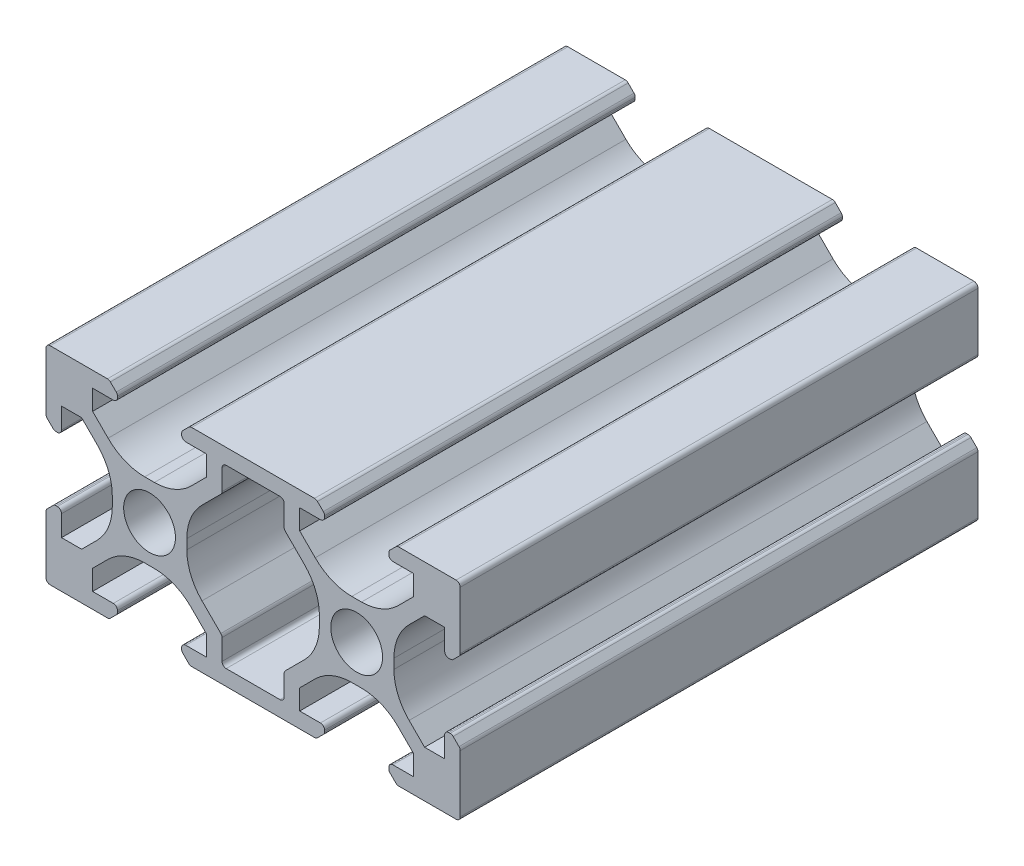
SolidWorks part; units mm, degrees
material "6063-T83"
ref_plane "Plano frontal" through (0, 0, 0) normal (0, 0, 1) x (1, 0, 0)
ref_plane "Plano superior" through (0, 0, 0) normal (0, 1, 0) x (1, 0, 0)
ref_plane "Plano direito" through (0, 0, 0) normal (1, 0, 0) x (0, 0, -1)
sketch "Esboço1" plane through (0, 0, 0) normal (0, 0, 1) x (1, 0, 0)
  line L0 (-9.0343, 3.1) -> (-8.9, 3.1)
  line L3 (-10, 10) -> (-4.0657, 10)
  line L5 (-10, -10) -> (10, 10) construction
  line L6 (-10, 10) -> (10, -10) construction
  line L7 (-8.5, 3.5) -> (-8.5, 5.5)
  line L8 (-10, 0) -> (10, 0) construction
  line L9 (0, 10) -> (0, -10) construction
  line L12 (-8.5, 5.5) -> (-6.5607, 5.5)
  line L15 (-6.5607, 5.5) -> (-5.0645, 4.0038)
  line L16 (-3.6, 0.4683) -> (-3.6, 0)
  line L17 (-0.4683, 3.6) -> (0, 3.6)
  line L18 (-5.5, 6.5607) -> (-4.0038, 5.0645)
  line L21 (-5.5, 8.5) -> (-5.5, 6.5607)
  line L24 (-3.5, 8.5) -> (-5.5, 8.5)
  line L25 (-3.1, 9.0343) -> (-3.1, 8.9)
  line L44 (-10, 4.0657) -> (-10, 10)
  line L45 (-9.8828, 3.7828) -> (-9.3172, 3.2172)
  line L46 (-3.7828, 9.8828) -> (-3.2172, 9.3172)
  line L47 (-3.6, 0) -> (-2.5, 0)
  line L48 (0, 3.6) -> (0, 2.5)
  arc A0 (-3.5, 8.5) -> (-3.1, 8.9) centre (-3.5, 8.9) ccw
  arc A1 (-3.7828, 9.8828) -> (-4.0657, 10) centre (-4.0657, 9.6) ccw
  arc A2 (-10, 4.0657) -> (-9.8828, 3.7828) centre (-9.6, 4.0657) ccw
  arc A3 (-8.5, 3.5) -> (-8.9, 3.1) centre (-8.9, 3.5) cw
  arc A4 (-3.2172, 9.3172) -> (-3.1, 9.0343) centre (-3.5, 9.0343) cw
  arc A5 (-9.3172, 3.2172) -> (-9.0343, 3.1) centre (-9.0343, 3.5) ccw
  arc A6 (-3.6, 0.4683) -> (-5.0645, 4.0038) centre (-8.6, 0.4683) ccw
  arc A7 (-4.0038, 5.0645) -> (-0.4683, 3.6) centre (-0.4683, 8.6) ccw
  circle A8 centre (0, 0) radius 2.5
  point P6 (-10, 3.1)
  point P28 (-3.1, 8.5)
  point P31 (-3.1, 10)
  point P33 (-3.9, 10)
  point P36 (-10, 3.9)
  point P39 (-8.5, 3.1)
  point P42 (-3.1, 9.2)
  point P45 (-9.2, 3.1)
  point P48 (-3.6, 2.5393)
  point P51 (-2.5393, 3.6)
  dimension "D5" = 10
  dimension "D9" = 0.4
  dimension "D10" = 0.4
  dimension "D11" = 5
  dimension "D12" = 5
  dimension "D13" = 5
  dimension "D1" = 6.9
  dimension "D2" = 1.5
  dimension "D3" = 3.6
  dimension "D4" = 1.5
  dimension "D6" = 2.4
  dimension "D7" = 3.6
  dimension "D8" = 45
extrude "Ressalto-extrusão1" add sketch "Esboço1" along normal blind 50
sketch "Esboço3" plane through (0, 0, 0) normal (1, 0, 0) x (0, 0, -1)
  line L0 (0, 0) -> (-1000, 0) construction
  dimension "D1" = 1000
pattern_circular "PadrãoCircular1" count 4 every 90 about axis through (0, 0, 0) along (0, 0, 1) of "Ressalto-extrusão1"
pattern_linear "Padrão linear1" count 2 spacing 20 along (1, 0, 0) of "Ressalto-extrusão1", "PadrãoCircular1"
sketch "Esboço4" plane through (0, 0, 0) normal (0, 0, -1) x (-1, 0, 0)
  line L0 (-13.4393, 5.5) -> (-13, 5.9393)
  line L1 (-13, 8.5) -> (-13, 5.9393)
  line L2 (-10, 10) -> (-10, -10) construction
  line L3 (-4.0657, 10) -> (-15.9343, 10) construction
  line L4 (-15.9343, -10) -> (-4.0657, -10) construction
  line L5 (-11.5, 5.5) -> (-13.4393, 5.5) construction
  line L6 (-14.5, 8.5) -> (-14.5, 6.5607) construction
  line L7 (-7, 8.5) -> (-7, 5.9393)
  line L8 (-6.5607, 5.5) -> (-7, 5.9393)
  line L9 (-13, 8.5) -> (-7, 8.5)
  line L10 (-20, 0) -> (0, 0) construction
  line L11 (-13, -8.5) -> (-7, -8.5)
  line L12 (-6.5607, -5.5) -> (-7, -5.9393)
  line L13 (-7, -8.5) -> (-7, -5.9393)
  line L14 (-13, -8.5) -> (-13, -5.9393)
  line L15 (-13.4393, -5.5) -> (-13, -5.9393)
  line L16 (-13.4393, 5.5) -> (-13.4393, -5.5)
  line L17 (-6.5607, -5.5) -> (-6.5607, 5.5)
  dimension "D1" = 45
  dimension "D2" = 1.5
  dimension "D3" = 1.5
extrude "Corte-extrusão1" cut sketch "Esboço4" against normal through all
fillet "Filete1" radius 0.4 8 edges at (13, -5.9393, 25) (13, -8.5, 25) (7, -8.5, 25) (7, -5.9393, 25) (7, 8.5, 25) (7, 5.9393, 25) (13, 8.5, 25) (13, 5.9393, 25)
fillet "Filete2" radius 0.4 4 edges at (30, -10, 25) (30, 10, 25) (-10, 10, 25) (-10, -10, 25)
